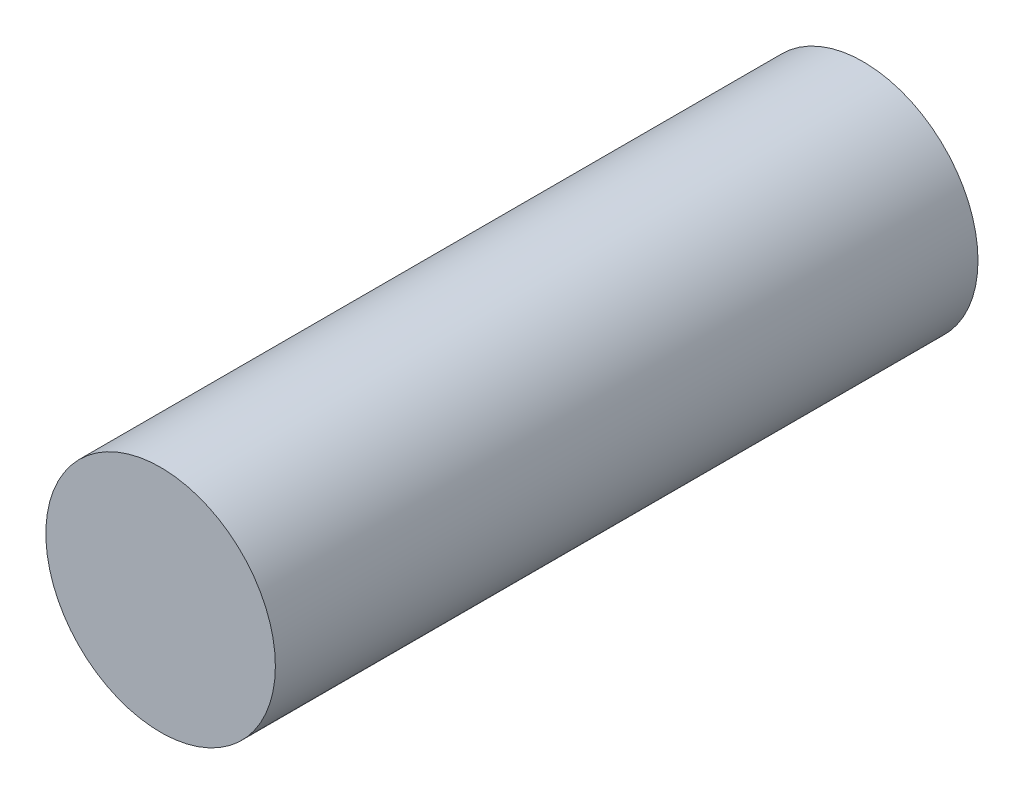
SolidWorks part; units mm, degrees
ref_plane "Płaszczyzna przednia" through (0, 0, 0) normal (0, 0, 1) x (1, 0, 0)
ref_plane "Płaszczyzna górna" through (0, 0, 0) normal (0, 1, 0) x (1, 0, 0)
ref_plane "Płaszczyzna prawa" through (0, 0, 0) normal (1, 0, 0) x (0, 0, -1)
sketch "Szkic1" plane through (0, 0, 0) normal (0, 0, 1) x (1, 0, 0)
  circle A0 centre (0, 0) radius 2.45
  point P4 (0, 0)
  dimension "D1" = 4.9
extrude "Dodanie-wyciągnięcie1" add sketch "Szkic1" along normal blind 15
